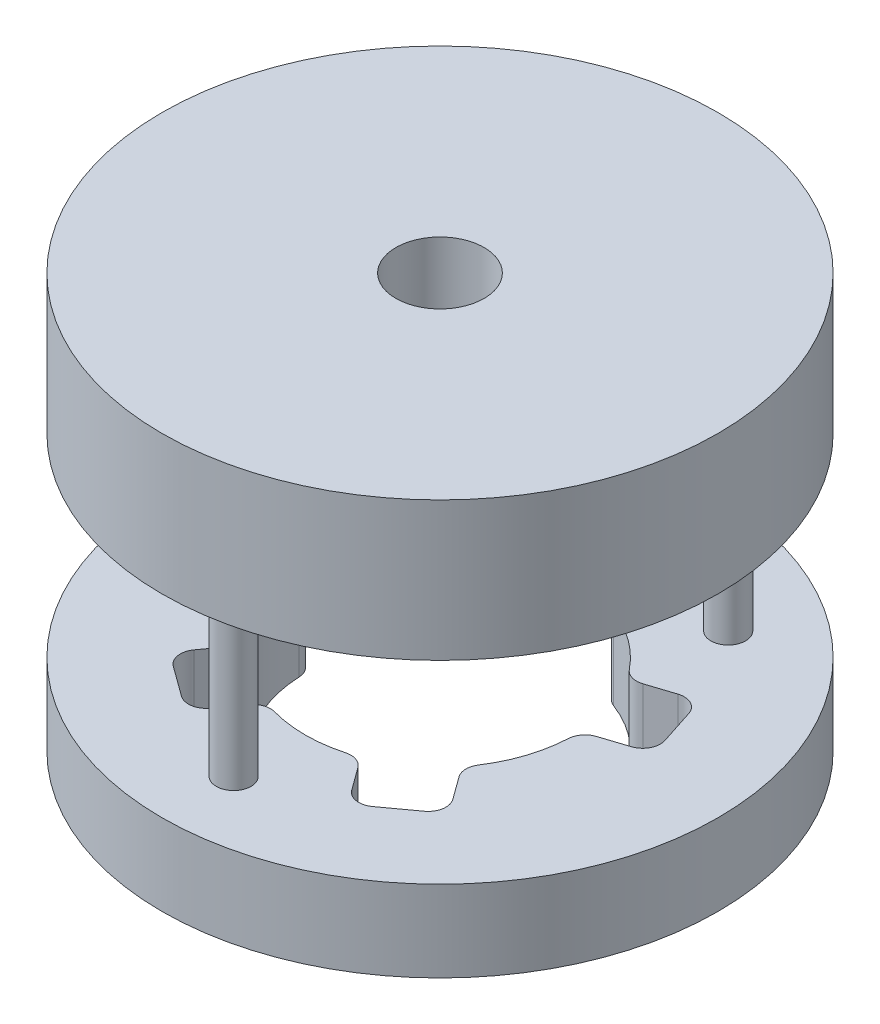
SolidWorks part; units mm, degrees
ref_plane "Front Plane" through (0, 0, 0) normal (0, 0, 1) x (1, 0, 0)
ref_plane "Top Plane" through (0, 0, 0) normal (0, 1, 0) x (1, 0, 0)
ref_plane "Right Plane" through (0, 0, 0) normal (1, 0, 0) x (0, 0, -1)
sketch "Sketch1" plane through (0, 0, 0) normal (0, 1, 0) x (1, 0, 0)
  line L0 (24.118, 13.3114) -> (27.3361, 3.4071)
  line L2 (-5.207, 18.669) -> (-5.207, 27.051)
  line L3 (-5.207, 27.051) -> (5.207, 27.051)
  line L4 (5.207, 18.669) -> (5.207, 27.051)
  line L7 (16.1462, 10.7212) -> (24.118, 13.3114)
  line L8 (19.3643, 0.8169) -> (27.3361, 3.4071)
  line L9 (20.1127, -18.8241) -> (11.6876, -24.9453)
  line L10 (15.1859, -12.0429) -> (20.1127, -18.8241)
  line L11 (6.7608, -18.1641) -> (11.6876, -24.9453)
  line L12 (-11.6876, -24.9453) -> (-20.1127, -18.8241)
  line L13 (-6.7608, -18.1641) -> (-11.6876, -24.9453)
  line L14 (-15.1859, -12.0429) -> (-20.1127, -18.8241)
  line L15 (-27.3361, 3.4071) -> (-24.118, 13.3114)
  line L16 (-19.3643, 0.8169) -> (-27.3361, 3.4071)
  line L17 (-16.1462, 10.7212) -> (-24.118, 13.3114)
  arc A0 (-5.207, 18.669) -> (-16.1462, 10.7212) centre (0, 0) ccw
  arc A1 (-19.3643, 0.8169) -> (-15.1859, -12.0429) centre (0, 0) ccw
  arc A2 (-6.7608, -18.1641) -> (6.7608, -18.1641) centre (0, 0) ccw
  arc A3 (15.1859, -12.0429) -> (19.3643, 0.8169) centre (0, 0) ccw
  arc A4 (16.1462, 10.7212) -> (5.207, 18.669) centre (0, 0) ccw
  circle A5 centre (0, 0) radius 6.35
  circle A6 centre (0, 0) radius 40
  circle A7 centre (0, 0) radius 27.051 construction
  point P9 (0, 27.051)
  point P26 (0, 0)
  dimension "D1" = 54.102
  dimension "D6" = 12.7
  dimension "D7" = 80
  dimension "D4" = 10.414
  dimension "D5" = 8.382
  dimension "D3" = 5
extrude "Boss-Extrude1" add sketch "Sketch1" along normal blind 11.684 contours A6 A4 L7 L0 L8 A3 L10 L9 L11 A2 L13 L12 L14 A1 L16 L15 L17 A0 L2 L3 L4
sketch "Sketch2" plane through (0, 11.684, 0) normal (0, 1, 0) x (1, 0, 0)
  line L0 (0, 0) -> (-11.3922, 15.68) construction
  line L1 (-11.3922, 15.68) -> (-23.5114, 32.3607) construction
  line L2 (0, 0) -> (11.3922, 15.68) construction
  line L3 (11.3922, 15.68) -> (23.5114, 32.3607) construction
  line L4 (0, 0) -> (0, -19.3815) construction
  line L5 (0, -19.3815) -> (0, -40) construction
  arc A0 (-5.207, 18.669) -> (-16.1462, 10.7212) centre (0, 0) ccw construction
  circle A1 centre (0, 0) radius 40 construction
  circle A2 centre (-17.4518, 24.0203) radius 2.5
  arc A3 (16.1462, 10.7212) -> (5.207, 18.669) centre (0, 0) ccw construction
  arc A4 (-6.7608, -18.1641) -> (6.7608, -18.1641) centre (0, 0) ccw construction
  circle A5 centre (17.4518, 24.0203) radius 2.5
  circle A6 centre (0, -29.6908) radius 2.5
  dimension "D1" = 5
extrude "Boss-Extrude2" add sketch "Sketch2" along normal blind 27.888
sketch "Sketch3" plane through (0, 39.572, 0) normal (0, 1, 0) x (1, 0, 0)
  circle A0 centre (0, 0) radius 40 construction
  circle A1 centre (0, 0) radius 40
extrude "Boss-Extrude3" add sketch "Sketch3" along normal blind 20
fillet "Fillet1" radius 2.54 20 edges at (-16.1462, 5.842, -10.7212) (-24.118, 5.842, -13.3114) (-27.3361, 5.842, -3.4071) (-19.3643, 5.842, -0.8169) (-20.1127, 5.842, 18.8241) (-15.1859, 5.842, 12.0429) (-11.6876, 5.842, 24.9453) (-6.7608, 5.842, 18.1641) (6.7608, 5.842, 18.1641) (11.6876, 5.842, 24.9453) (20.1127, 5.842, 18.8241) (15.1859, 5.842, 12.0429) (19.3643, 5.842, -0.8169) (27.3361, 5.842, -3.4071) (16.1462, 5.842, -10.7212) (24.118, 5.842, -13.3114) (5.207, 5.842, -18.669) (5.207, 5.842, -27.051) (-5.207, 5.842, -18.669) (-5.207, 5.842, -27.051)
sketch "Sketch4" plane through (0, 59.572, 0) normal (0, 1, 0) x (1, 0, 0)
  circle A0 centre (0, 0) radius 6.35
  dimension "D1" = 12.7
extrude "Cut-Extrude1" cut sketch "Sketch4" against normal up to next
